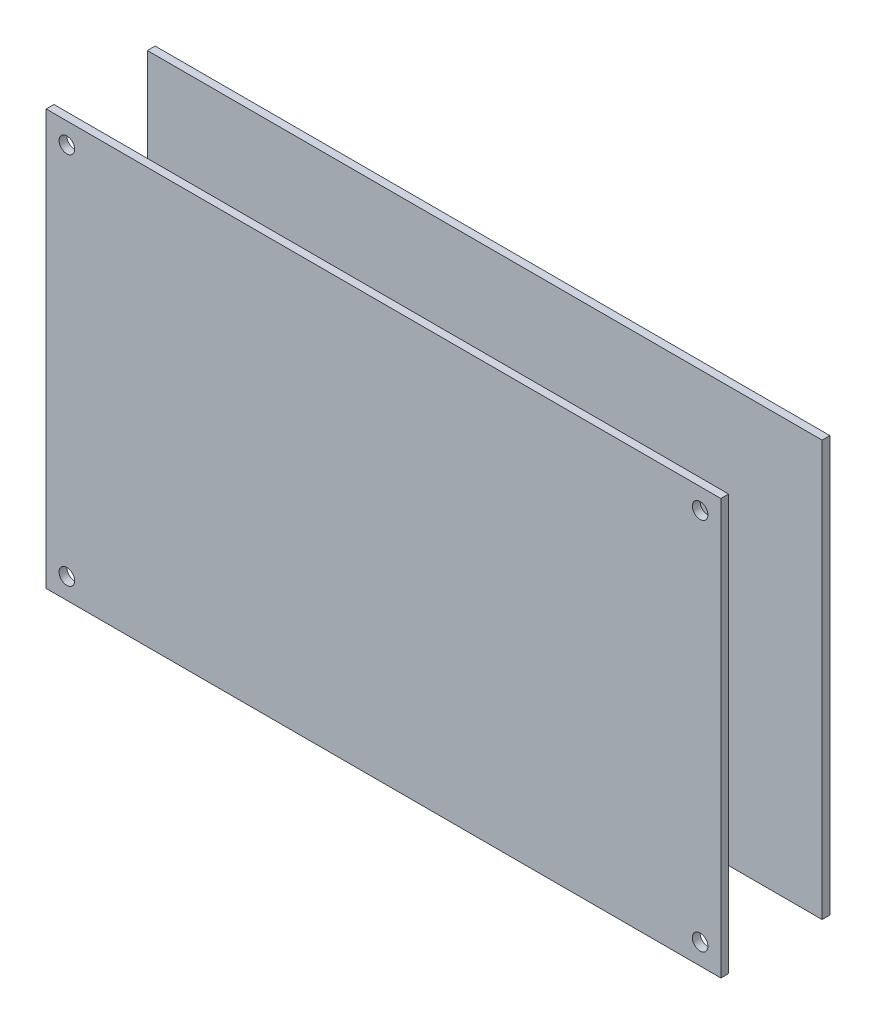
SolidWorks part; units mm, degrees
ref_plane "Plan de face" through (0, 0, 0) normal (0, 0, 1) x (1, 0, 0)
ref_plane "Plan de dessus" through (0, 0, 0) normal (0, 1, 0) x (1, 0, 0)
ref_plane "Plan de droite" through (0, 0, 0) normal (1, 0, 0) x (0, 0, -1)
sketch "Esquisse1" plane through (0, 0, 0) normal (0, 0, 1) x (1, 0, 0)
  line L1 (0, 0) -> (130, 0)
  line L2 (0, 0) -> (0, 80)
  line L3 (0, 80) -> (130, 80)
  line L4 (130, 0) -> (130, 80)
  dimension "D1" = 80
  dimension "D2" = 130
extrude "Boss.-Extru.1" add sketch "Esquisse1" along normal blind 21
shell "Coque3" thickness 1.5
sketch "Esquisse2" plane through (0, 0, 0) normal (0, 0, -1) x (-1, 0, 0)
  line L1 (-116.9103, 73.738) -> (-11.4103, 73.738)
  line L2 (-116.9103, 73.738) -> (-116.9103, 5.938)
  line L3 (-116.9103, 5.938) -> (-11.4103, 5.938)
  line L4 (-11.4103, 73.738) -> (-11.4103, 5.938)
  dimension "D1" = 67.8
  dimension "D2" = 105.5
extrude "Boss.-Extru.2" add sketch "Esquisse2" along normal blind 5 contours L2 L1 L4 L3
sketch "Esquisse3" plane through (0, 0, 21) normal (0, 0, 1) x (1, 0, 0)
  line L0 (0, 80) -> (0, 0) construction
  line L1 (4, 76) -> (126, 76) construction
  line L2 (4, 76) -> (4, 4) construction
  line L3 (4, 4) -> (126, 4) construction
  line L4 (126, 76) -> (126, 4) construction
  line L5 (130, 80) -> (0, 80) construction
  circle A0 centre (4, 76) radius 1.5
  circle A1 centre (4, 4) radius 1.5
  circle A2 centre (126, 76) radius 1.5
  circle A3 centre (126, 4) radius 1.5
  point P11 (0, 40)
  point P12 (4, 40)
  point P15 (65, 80)
  point P16 (65, 76)
  dimension "D1" = 72
  dimension "D2" = 122
extrude "Enlèv. mat.-Extru.1" cut sketch "Esquisse3" against normal blind 10
sketch "Esquisse4" plane through (0, 78.5, 0) normal (0, -1, 0) x (1, 0, 0)
  line L1 (0, 19.5) -> (130, 19.5)
  line L2 (0, 19.5) -> (0, 1.5)
  line L3 (0, 1.5) -> (130, 1.5)
  line L4 (130, 19.5) -> (130, 1.5)
extrude "Enlèv. mat.-Extru.2" cut sketch "Esquisse4" against normal blind 10
